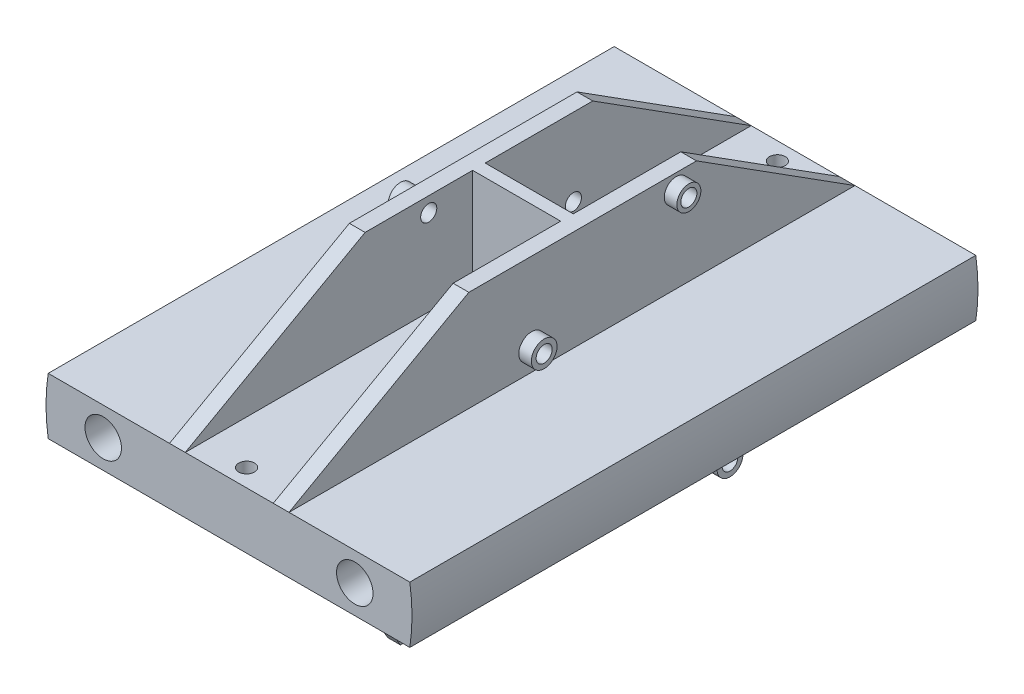
SolidWorks part; units mm, degrees
ref_plane "Front Plane" through (0, 0, 0) normal (0, 0, 1) x (1, 0, 0)
ref_plane "Top Plane" through (0, 0, 0) normal (0, 1, 0) x (1, 0, 0)
ref_plane "Right Plane" through (0, 0, 0) normal (1, 0, 0) x (0, 0, -1)
sketch "Sketch1" plane through (0, 0, 0) normal (0, 0, 1) x (1, 0, 0)
  line L0 (-25.4, 5.715) -> (25.4, 5.715)
  line L1 (-19.685, 0) -> (19.685, 0)
  line L2 (-25.4, 5.715) -> (-37.6689, 5.715)
  line L3 (25.4, 5.715) -> (37.6689, 5.715)
  line L4 (-31.115, 0) -> (-38.1, 0)
  line L5 (31.115, 0) -> (38.1, 0)
  line L6 (-25.4, -5.715) -> (25.4, -5.715)
  line L7 (25.4, -5.715) -> (37.6689, -5.715)
  line L8 (-25.4, -5.715) -> (-37.6689, -5.715)
  circle A0 centre (25.4, 0) radius 3.683
  circle A1 centre (-25.4, 0) radius 3.683
  circle A2 centre (-25.4, 0) radius 5.715
  circle A3 centre (25.4, 0) radius 5.715
  circle A4 centre (0, 0) radius 38.1
  dimension "D3" = 7.366
  dimension "D4" = 11.43
  dimension "D5" = 11.43
  dimension "D6" = 76.2
  dimension "D1" = 25.4
  dimension "D2" = 25.4
extrude "Boss-Extrude2" add sketch "Sketch1" along normal blind 114.3 contours A3 L0 A2 L1 | A2 A1 | A3 A0 | L2 A4 L4 A2 | L5 A4 L3 A3 | L7 A4 L5 A3 | A3 L1 A2 L6 | L4 A4 L8 A2
sketch "Sketch2" plane through (0, 5.715, 0) normal (0, 1, 0) x (1, 0, 0)
  line L11 (-22.1921, 2.7781) -> (-22.225, 2.8638) construction
  line L12 (-22.1921, 0) -> (-22.1921, 5.5562) construction
  line L13 (-22.225, -212.6615) -> (-22.225, 92.1385) construction
  line L14 (22.1921, 0) -> (22.1921, 5.5562) construction
  line L15 (22.1921, 2.7781) -> (22.225, 2.8645) construction
  line L16 (22.225, 92.1385) -> (22.225, -212.6615) construction
  line L21 (-8.8399, -32.004) -> (-12.0149, -32.004)
  line L22 (-8.8399, -32.004) -> (-8.8399, -77.978)
  line L23 (-8.8399, -77.978) -> (-12.0149, -77.978)
  line L24 (-12.0149, -32.004) -> (-12.0149, -77.978)
  line L25 (8.9401, -32.004) -> (12.1151, -32.004)
  line L26 (8.9401, -32.004) -> (8.9401, -77.978)
  line L27 (8.9401, -77.978) -> (12.1151, -77.978)
  line L28 (12.1151, -32.004) -> (12.1151, -77.978)
extrude "Boss-Extrude3" add sketch "Sketch2" along normal blind 20.32
sketch "Sketch8" plane through (0, 5.715, 0) normal (0, 1, 0) x (1, 0, 0)
  line L0 (-8.8399, -77.978) -> (-8.8399, -32.004) construction
  line L1 (-8.8399, -53.721) -> (8.9401, -53.721)
  line L2 (-8.8399, -53.721) -> (-8.8399, -56.261)
  line L3 (-8.8399, -56.261) -> (8.9401, -56.261)
  line L4 (8.9401, -53.721) -> (8.9401, -56.261)
  line L5 (8.9401, -32.004) -> (8.9401, -77.978) construction
  line L7 (12.1151, -32.004) -> (8.9401, -32.004) construction
  dimension "D1" = 2.54
  dimension "D2" = 21.717
extrude "Boss-Extrude6" add sketch "Sketch8" along normal up to surface (20.32 mm away) up to face at (-10.4274, 26.035, 54.991)
sketch "Sketch9" plane through (0, -5.715, 0) normal (0, -1, 0) x (1, 0, 0)
  line L2 (12.2689, 73.66) -> (12.2689, 17.78)
  line L3 (12.2689, 17.78) -> (14.8089, 17.78)
  line L4 (14.8089, 17.78) -> (14.8089, 106.68)
  line L5 (14.8089, 106.68) -> (12.2689, 106.68)
  line L6 (12.2689, 106.68) -> (12.2689, 76.2)
  line L7 (12.2689, 76.2) -> (-27.5089, 76.2)
  line L8 (-27.5089, 76.2) -> (-27.5089, 106.68)
  line L9 (-27.5089, 106.68) -> (-30.0489, 106.68)
  line L10 (-30.0489, 106.68) -> (-30.0489, 17.78)
  line L11 (-30.0489, 17.78) -> (-27.5089, 17.78)
  line L12 (-27.5089, 17.78) -> (-27.5089, 73.66)
  line L14 (-37.6689, 0) -> (37.6689, 0) construction
  line L15 (37.6689, 114.3) -> (37.6689, 0) construction
  line L16 (-37.6689, 114.3) -> (-37.6689, 0) construction
  line L17 (-27.5089, 73.66) -> (12.2689, 73.66)
  dimension "D2" = 2.54
  dimension "D3" = 2.54
  dimension "D4" = 17.78
  dimension "D5" = 17.78
  dimension "D6" = 30.48
  dimension "D7" = 30.48
  dimension "D8" = 2.54
  dimension "D9" = 2.54
  dimension "D10" = 22.86
  dimension "D11" = 7.62
  dimension "D12" = 2.54
extrude "Boss-Extrude9" add sketch "Sketch9" along normal blind 20.32
sketch "Sketch10" plane through (14.8089, 0, 0) normal (1, 0, 0) x (0, 0, -1)
  line L0 (-106.68, -26.035) -> (-106.68, -5.715) construction
  line L1 (-17.78, -5.715) -> (-106.68, -5.715) construction
  circle A0 centre (-58.42, -9.525) radius 1.5875
  circle A1 centre (-33.02, -22.225) radius 1.5875
  dimension "D2" = 3.175
  dimension "D1" = 12.7
  dimension "D3" = 25.4
  dimension "D4" = 48.26
  dimension "D5" = 3.81
extrude "Cut-Extrude5" cut sketch "Sketch10" against normal up to next
sketch "Sketch12" plane through (14.8089, 0, 0) normal (1, 0, 0) x (0, 0, -1)
  circle A0 centre (-58.42, -9.525) radius 2.5903
  circle A1 centre (-33.02, -22.225) radius 2.6122
  circle A2 centre (-33.02, -22.225) radius 1.5875
  circle A3 centre (-58.42, -9.525) radius 1.5875
sketch "Sketch13" plane through (0, -5.715, 0) normal (0, -1, 0) x (1, 0, 0)
  line L0 (-37.6689, 114.3) -> (37.6689, 114.3) construction
  line L1 (-37.6689, 0) -> (37.6689, 0) construction
  circle A0 centre (0, 110.744) radius 1.5875
  circle A1 centre (0, 3.556) radius 1.5875
  dimension "D1" = 3.175
  dimension "D3" = 3.175
  dimension "D2" = 3.556
  dimension "D4" = 3.556
extrude "Cut-Extrude6" cut sketch "Sketch13" against normal up to next
sketch "Sketch18" plane through (-12.0149, 0, 0) normal (-1, 0, 0) x (0, 0, 1)
  line L0 (77.978, 5.715) -> (77.978, 26.035)
  line L1 (77.978, 26.035) -> (114.3, 5.715)
  line L2 (114.3, 5.715) -> (0, 5.715) construction
  line L3 (114.3, 5.715) -> (77.978, 5.715)
  line L4 (32.004, 26.035) -> (32.004, 5.715)
  line L5 (32.004, 5.715) -> (0, 5.715)
  line L6 (0, 5.715) -> (32.004, 26.035)
extrude "Boss-Extrude14" add sketch "Sketch18" against normal up to surface (3.175 mm away) up to face at (-8.8399, 15.875, 42.8625)
sketch "Sketch19" plane through (12.1151, 0, 0) normal (1, 0, 0) x (0, 0, -1)
  line L0 (-32.004, 26.035) -> (0, 5.715)
  line L1 (0, 5.715) -> (-32.004, 5.715)
  line L2 (-32.004, 5.715) -> (-32.004, 26.035)
  line L3 (-77.978, 5.715) -> (-114.3, 5.715)
  line L4 (-77.978, 26.035) -> (-114.3, 5.715) construction
  line L5 (-114.3, 5.715) -> (-56.261, 5.715) construction
  line L6 (-114.3, 5.715) -> (-77.978, 26.035)
  line L7 (-77.978, 26.035) -> (-77.978, 5.715)
extrude "Boss-Extrude15" add sketch "Sketch19" against normal up to surface (3.175 mm away) up to face at (8.9401, 15.875, 67.1195)
extrude "Boss-Extrude16" add sketch "Sketch12" along normal blind 5.08
chamfer "Chamfer1" distance 2.54 angle 45 1 edges at (-30.0489, -26.035, 62.23)
sketch "Sketch21" plane through (-12.0149, 0, 0) normal (-1, 0, 0) x (0, 0, 1)
  circle A0 centre (65.1252, 23.0376) radius 1.6256
  circle A1 centre (35.9152, 10.3376) radius 1.6256
extrude "Cut-Extrude7" cut sketch "Sketch21" against normal blind 5.08
sketch "Sketch22" plane through (12.1151, 0, 0) normal (1, 0, 0) x (0, 0, -1)
  circle A0 centre (-36.0927, 22.9116) radius 1.6256
  circle A1 centre (-65.3027, 10.2116) radius 1.6256
extrude "Cut-Extrude8" cut sketch "Sketch22" against normal blind 5.08
sketch "Sketch23" plane through (12.1151, 0, 0) normal (1, 0, 0) x (0, 0, -1)
  circle A0 centre (-36.0927, 22.9116) radius 1.6256
  circle A1 centre (-36.0927, 22.9116) radius 2.4266
  circle A2 centre (-65.3027, 10.2116) radius 1.6256
  circle A3 centre (-65.3027, 10.2116) radius 2.5985
extrude "Boss-Extrude17" add sketch "Sketch23" along normal blind 2.54
sketch "Sketch24" plane through (-12.0149, 0, 0) normal (-1, 0, 0) x (0, 0, 1)
  circle A0 centre (65.1252, 23.0376) radius 1.6256
  circle A1 centre (65.1252, 23.0376) radius 2.468
  circle A2 centre (35.9152, 10.3376) radius 1.6256
  circle A3 centre (35.9152, 10.3376) radius 2.5333
extrude "Boss-Extrude18" add sketch "Sketch24" along normal blind 2.54
sketch "Sketch25" plane through (0, 0, 0) normal (0, 0, -1) x (-1, 0, 0)
  circle A0 centre (0, 0) radius 48.7716
  circle A1 centre (0, 0) radius 36.957
  dimension "D1" = 73.914
extrude "Cut-Extrude9" cut sketch "Sketch25" against normal through all
sketch "Sketch26" plane through (14.8089, 0, 0) normal (1, 0, 0) x (0, 0, -1)
  line L1 (-59.69, -26.035) -> (-19.558, -26.035) construction
  line L2 (-29.972, -26.035) -> (-17.78, -5.715)
  line L8 (-29.972, -26.035) -> (-17.78, -26.035)
  line L9 (-17.78, -26.035) -> (-17.78, -5.715)
  line L10 (-106.68, -5.715) -> (-106.68, -26.035)
  line L11 (-106.68, -26.035) -> (-94.488, -26.035)
  line L12 (-17.78, -26.035) -> (-106.68, -26.035) construction
  line L13 (-94.488, -26.035) -> (-106.68, -5.715)
  dimension "D1" = 12.192
  dimension "D2" = 12.192
extrude "Cut-Extrude10" cut sketch "Sketch26" against normal through all
